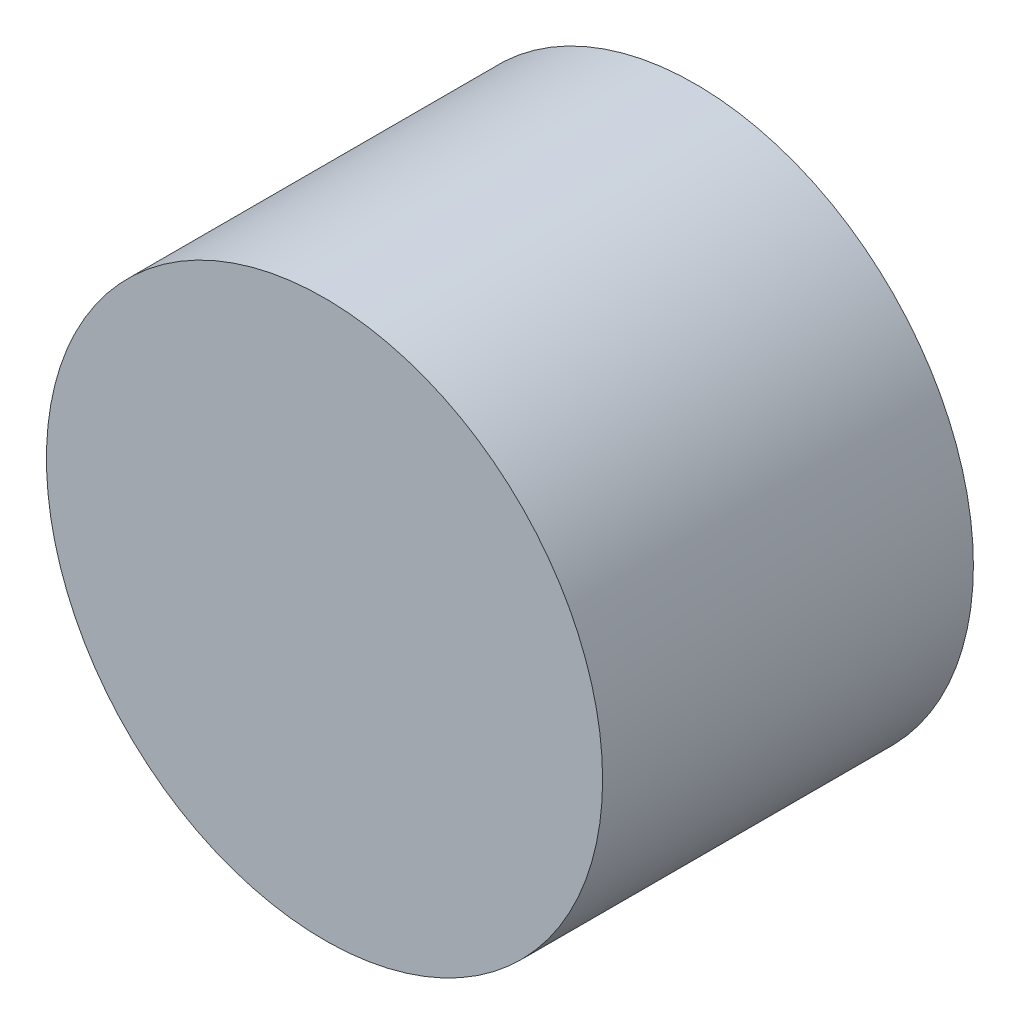
SolidWorks part; units mm, degrees
ref_plane "Alzado" through (0, 0, 0) normal (0, 0, 1) x (1, 0, 0)
ref_plane "Planta" through (0, 0, 0) normal (0, 1, 0) x (1, 0, 0)
ref_plane "Vista lateral" through (0, 0, 0) normal (1, 0, 0) x (0, 0, -1)
sketch "Croquis1" plane through (0, 0, 0) normal (0, 0, 1) x (1, 0, 0)
  circle A0 centre (0, 0) radius 12
  dimension "D1" = 24
extrude "Saliente-Extruir1" add sketch "Croquis1" along normal blind 16
ref_plane "Plano1" through (-12, 0, 0) normal (-1, 0, 0) x (0, 0, 1)
sketch "Croquis3" plane through (-12, 0, 0) normal (-1, 0, 0) x (0, 0, 1)
  line L0 (16, -12) -> (16, 12) construction
  line L1 (1, -6) -> (7, -6)
  line L2 (1, -6) -> (1, 6)
  line L3 (1, 6) -> (7, 6)
  line L4 (7, -6) -> (7, 6)
  line L5 (1, -6) -> (7, 6) construction
  line L6 (1, 6) -> (7, -6) construction
  point P0 (4, 0)
  dimension "D1" = 6
  dimension "D2" = 12
  dimension "D3" = 9
extrude "Cortar-Extruir1" cut sketch "Croquis3" against normal blind 9 and the other way blind 1
